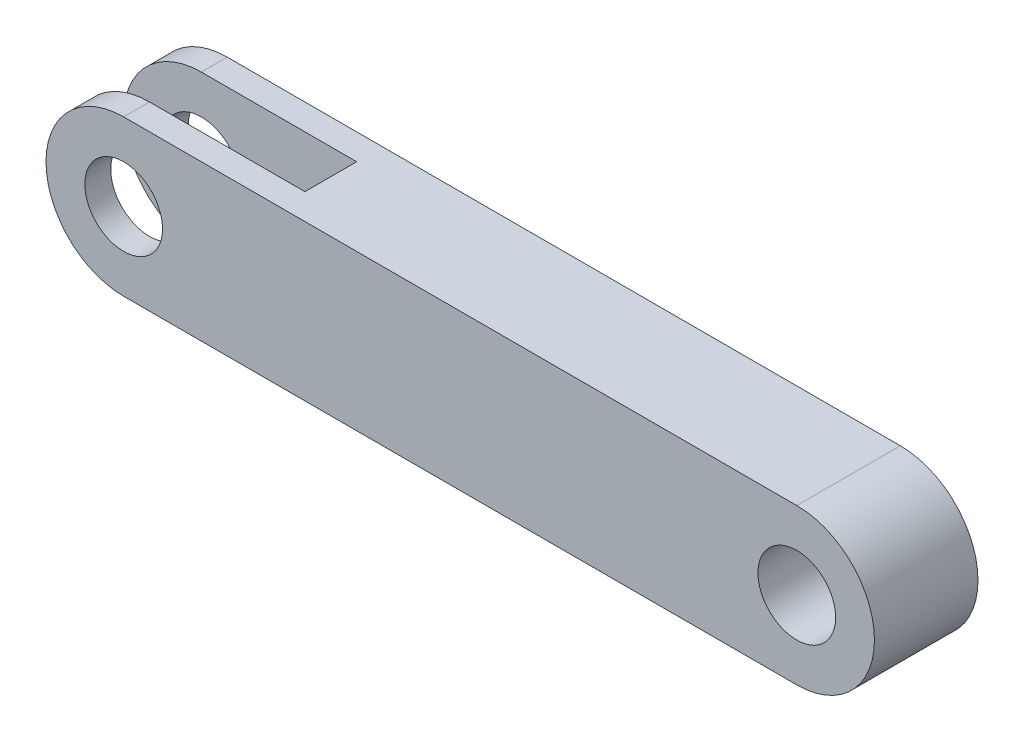
SolidWorks part; units mm, degrees
ref_plane "前视基准面" through (0, 0, 0) normal (0, 0, 1) x (1, 0, 0)
ref_plane "上视基准面" through (0, 0, 0) normal (0, 1, 0) x (1, 0, 0)
ref_plane "右视基准面" through (0, 0, 0) normal (1, 0, 0) x (0, 0, -1)
sketch "草图1" plane through (0, 0, 0) normal (0, 0, 1) x (1, 0, 0)
  line L0 (-26, 0) -> (26, 0) construction
  line L1 (-26, 6) -> (26, 6)
  line L2 (-26, -6) -> (26, -6)
  arc A0 (-26, 6) -> (-26, -6) centre (-26, 0) ccw
  arc A1 (26, -6) -> (26, 6) centre (26, 0) ccw
  circle A2 centre (-26, 0) radius 3
  circle A3 centre (26, 0) radius 3
  point P3 (0, 0)
  dimension "D3" = 6
  dimension "D4" = 6
  dimension "D1" = 12
  dimension "D2" = 52
extrude "凸台-拉伸1" add sketch "草图1" along normal blind 8
sketch "草图2" plane through (0, 6, 0) normal (0, 1, 0) x (1, 0, 0)
  line L0 (-26, 0) -> (-32, 0) construction
  line L1 (-32, -2) -> (-14, -2)
  line L2 (-32, -2) -> (-32, -6)
  line L3 (-32, -6) -> (-14, -6)
  line L4 (-14, -2) -> (-14, -6)
  line L5 (-26, -8) -> (-26, 0) construction
  dimension "D1" = 4
  dimension "D2" = 2
  dimension "D3" = 6
  dimension "D4" = 18
extrude "切除-拉伸1" cut sketch "草图2" against normal through all
